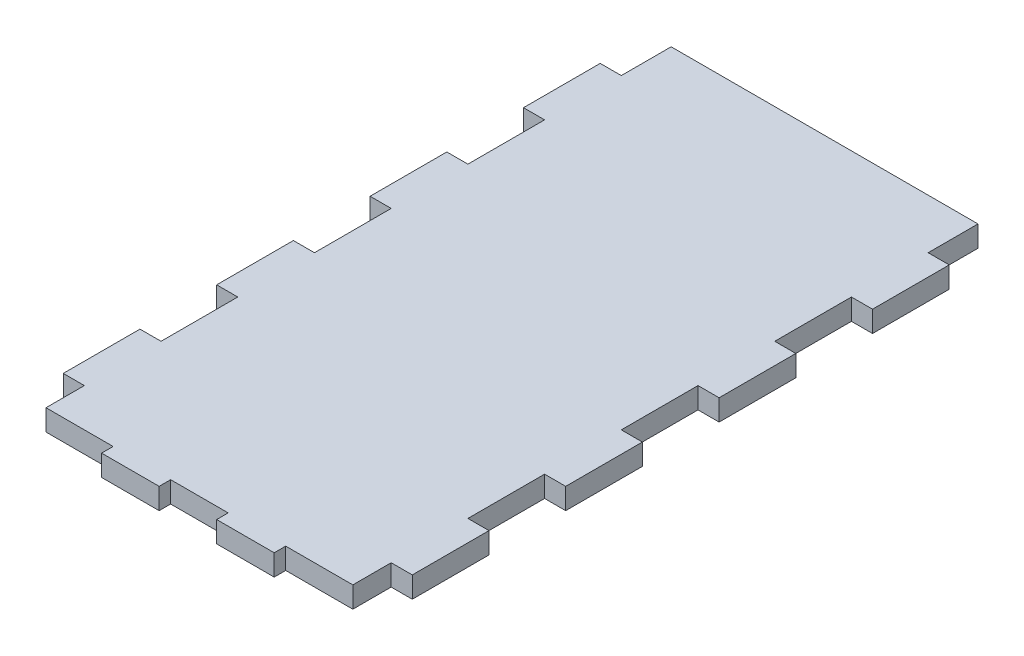
SolidWorks part; units mm, degrees
ref_plane "Alzado" through (0, 0, 0) normal (0, 0, 1) x (1, 0, 0)
ref_plane "Planta" through (0, 0, 0) normal (0, 1, 0) x (1, 0, 0)
ref_plane "Vista lateral" through (0, 0, 0) normal (1, 0, 0) x (0, 0, -1)
sketch "Croquis1" plane through (0, 0, 0) normal (0, 1, 0) x (1, 0, 0)
  line L0 (23, 0) -> (38, 0)
  line L1 (91, 13) -> (91, 33)
  line L2 (85.5, 166) -> (5.5, 166)
  line L3 (0, 153) -> (0, 93)
  line L5 (5.5, 73) -> (5.5, 93)
  line L6 (5.5, 93) -> (0, 93)
  line L7 (0, 93) -> (0, 113)
  line L8 (0, 113) -> (5.5, 113)
  line L9 (5.5, 113) -> (5.5, 133)
  line L10 (5.5, 133) -> (0, 133)
  line L11 (0, 133) -> (0, 153)
  line L12 (0, 153) -> (5.5, 153)
  line L13 (0, 13) -> (5.5, 13)
  line L14 (5.5, 33) -> (0, 33)
  line L15 (5.5, 53) -> (5.5, 33)
  line L16 (0, 53) -> (5.5, 53)
  line L17 (5.5, 73) -> (0, 73)
  line L18 (5.5, 153) -> (5.5, 166)
  line L19 (5.5, 13) -> (5.5, 3)
  line L20 (0, 33) -> (0, 13)
  line L21 (53, 3) -> (38, 3)
  line L22 (38, 3) -> (38, 0)
  line L23 (38, 0) -> (23, 0)
  line L24 (23, 0) -> (23, 3)
  line L25 (23, 3) -> (5.5, 3)
  line L26 (68, 3) -> (85.5, 3)
  line L27 (68, 0) -> (68, 3)
  line L28 (53, 3) -> (53, 0)
  line L29 (85.5, 13) -> (85.5, 3)
  line L30 (85.5, 153) -> (85.5, 166)
  line L31 (85.5, 73) -> (91, 73)
  line L32 (91, 53) -> (85.5, 53)
  line L33 (85.5, 53) -> (85.5, 33)
  line L34 (85.5, 33) -> (91, 33)
  line L35 (91, 13) -> (85.5, 13)
  line L36 (91, 153) -> (85.5, 153)
  line L37 (85.5, 133) -> (91, 133)
  line L38 (85.5, 113) -> (85.5, 133)
  line L39 (91, 113) -> (85.5, 113)
  line L40 (85.5, 93) -> (91, 93)
  line L41 (85.5, 73) -> (85.5, 93)
  line L42 (91, 133) -> (91, 153)
  line L43 (53, 0) -> (68, 0)
  line L44 (91, 53) -> (91, 73)
  line L45 (91, 93) -> (91, 113)
  line L46 (0, 73) -> (0, 53)
  dimension "D5" = 20
  dimension "D6" = 20
  dimension "D7" = 20
  dimension "D10" = 15
extrude "Saliente-Extruir1" add sketch "Croquis1" along normal blind 5.5
